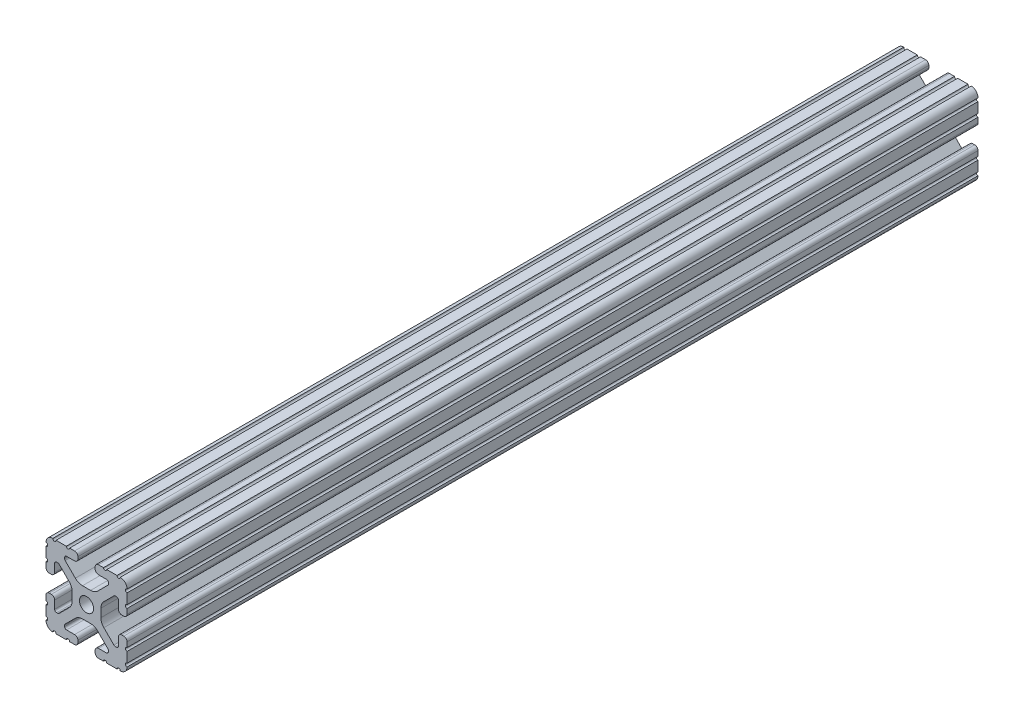
SolidWorks part; units mm, degrees
ref_plane "Front Plane" through (0, 0, 0) normal (0, 0, 1) x (1, 0, 0)
ref_plane "Top Plane" through (0, 0, 0) normal (0, 1, 0) x (1, 0, 0)
ref_plane "Right Plane" through (0, 0, 0) normal (1, 0, 0) x (0, 0, -1)
ref_plane "Plane1" through (0, 0, -304.8) normal (0, 0, -1) x (-1, 0, 0)
sketch "Sketch1" plane through (0, 0, -304.8) normal (0, 0, -1) x (-1, 0, 0)
  line L0 (14.3277, 19.05) -> (9.4982, 19.05)
  line L1 (7.9742, 19.05) -> (5.6176, 19.05)
  line L2 (4.064, 17.4964) -> (4.064, 16.5396)
  line L3 (5.6176, 14.986) -> (9.3853, 14.986)
  line L4 (10.287, 14.0843) -> (10.287, 13.5524)
  line L5 (10.0229, 12.9148) -> (5.2522, 8.144)
  line L6 (1.9022, 6.7564) -> (-1.9022, 6.7564)
  line L7 (-5.2522, 8.144) -> (-10.0229, 12.9148)
  line L8 (-10.287, 13.5524) -> (-10.287, 14.0843)
  line L9 (-9.3853, 14.986) -> (-5.6176, 14.986)
  line L10 (-4.064, 16.5396) -> (-4.064, 17.4964)
  line L11 (-5.6176, 19.05) -> (-7.9742, 19.05)
  line L12 (-9.4982, 19.05) -> (-14.3277, 19.05)
  line L13 (-19.05, 14.3277) -> (-19.05, 9.4961)
  line L14 (-19.05, 7.9763) -> (-19.05, 5.6176)
  line L15 (-17.4964, 4.064) -> (-16.5396, 4.064)
  line L16 (-14.986, 5.6176) -> (-14.986, 9.3853)
  line L17 (-14.0843, 10.287) -> (-13.516, 10.287)
  line L18 (-12.8784, 10.0229) -> (-8.1476, 5.2921)
  line L19 (-6.7564, 1.9335) -> (-6.7564, -1.9335)
  line L20 (-8.1476, -5.2921) -> (-12.8784, -10.0229)
  line L21 (-13.516, -10.287) -> (-14.0843, -10.287)
  line L22 (-14.986, -9.3853) -> (-14.986, -5.6176)
  line L23 (-16.5396, -4.064) -> (-17.4964, -4.064)
  line L24 (-19.05, -5.6176) -> (-19.05, -7.9763)
  line L25 (-19.05, -9.4961) -> (-19.05, -14.3277)
  line L26 (-14.3277, -19.05) -> (-9.4961, -19.05)
  line L27 (-7.9763, -19.05) -> (-5.6176, -19.05)
  line L28 (-4.064, -17.4964) -> (-4.064, -16.5396)
  line L29 (-5.6176, -14.986) -> (-9.3853, -14.986)
  line L30 (-10.287, -14.0843) -> (-10.287, -13.5524)
  line L31 (-10.0229, -12.9148) -> (-5.2522, -8.144)
  line L32 (-1.9022, -6.7564) -> (1.9022, -6.7564)
  line L33 (5.2522, -8.144) -> (10.0229, -12.9148)
  line L34 (10.287, -13.5524) -> (10.287, -14.0843)
  line L35 (9.3853, -14.986) -> (5.6176, -14.986)
  line L36 (4.064, -16.5396) -> (4.064, -17.4964)
  line L37 (5.6176, -19.05) -> (7.9763, -19.05)
  line L38 (9.4961, -19.05) -> (14.3277, -19.05)
  line L39 (19.05, -14.3277) -> (19.05, -9.4961)
  line L40 (19.05, -7.9763) -> (19.05, -5.6176)
  line L41 (17.4964, -4.064) -> (16.5396, -4.064)
  line L42 (14.986, -5.6176) -> (14.986, -9.3853)
  line L43 (14.0843, -10.287) -> (13.516, -10.287)
  line L44 (12.8784, -10.0229) -> (8.1476, -5.2921)
  line L45 (6.7564, -1.9335) -> (6.7564, 1.9335)
  line L46 (8.1476, 5.2921) -> (12.8784, 10.0229)
  line L47 (13.516, 10.287) -> (14.0843, 10.287)
  line L48 (14.986, 9.3853) -> (14.986, 5.6176)
  line L49 (16.5396, 4.064) -> (17.4964, 4.064)
  line L50 (19.05, 5.6176) -> (19.05, 7.9763)
  line L51 (19.05, 9.4961) -> (19.05, 14.3277)
  line L52 (19.05, 5.6176) -> (17.4964, 5.6176) construction
  line L53 (17.4964, 5.6176) -> (17.4964, 4.064) construction
  line L54 (17.4964, 5.6176) -> (18.5393, 4.466) construction
  arc A0 (15.8475, 19.05) -> (14.3277, 19.05) centre (15.0876, 18.9933) cw
  arc A1 (9.4982, 19.05) -> (7.9742, 19.05) centre (8.7362, 19.05) cw
  arc A2 (5.6176, 19.05) -> (4.064, 17.4964) centre (5.6176, 17.4964) ccw
  arc A3 (4.064, 16.5396) -> (5.6176, 14.986) centre (5.6176, 16.5396) ccw
  arc A4 (9.3853, 14.986) -> (10.287, 14.0843) centre (9.3853, 14.0843) cw
  arc A5 (10.287, 13.5524) -> (10.0229, 12.9148) centre (9.3853, 13.5524) cw
  arc A6 (5.2522, 8.144) -> (1.9022, 6.7564) centre (1.9022, 11.494) cw
  arc A7 (-1.9022, 6.7564) -> (-5.2522, 8.144) centre (-1.9022, 11.494) cw
  arc A8 (-10.0229, 12.9148) -> (-10.287, 13.5524) centre (-9.3853, 13.5524) cw
  arc A9 (-10.287, 14.0843) -> (-9.3853, 14.986) centre (-9.3853, 14.0843) cw
  arc A10 (-5.6176, 14.986) -> (-4.064, 16.5396) centre (-5.6176, 16.5396) ccw
  arc A11 (-4.064, 17.4964) -> (-5.6176, 19.05) centre (-5.6176, 17.4964) ccw
  arc A12 (-7.9742, 19.05) -> (-9.4982, 19.05) centre (-8.7362, 19.05) cw
  arc A13 (-14.3277, 19.05) -> (-15.8475, 19.05) centre (-15.0876, 18.9933) cw
  arc A14 (-15.8475, 19.05) -> (-19.05, 15.8475) centre (-15.8751, 15.8751) ccw
  arc A15 (-19.05, 15.8475) -> (-19.05, 14.3277) centre (-18.9933, 15.0876) cw
  arc A16 (-19.05, 9.4961) -> (-19.05, 7.9763) centre (-18.9933, 8.7362) cw
  arc A17 (-19.05, 5.6176) -> (-17.4964, 4.064) centre (-17.4964, 5.6176) ccw
  arc A18 (-16.5396, 4.064) -> (-14.986, 5.6176) centre (-16.5396, 5.6176) ccw
  arc A19 (-14.986, 9.3853) -> (-14.0843, 10.287) centre (-14.0843, 9.3853) cw
  arc A20 (-13.516, 10.287) -> (-12.8784, 10.0229) centre (-13.516, 9.3853) cw
  arc A21 (-8.1476, 5.2921) -> (-6.7564, 1.9335) centre (-11.5062, 1.9335) cw
  arc A22 (-6.7564, -1.9335) -> (-8.1476, -5.2921) centre (-11.5062, -1.9335) cw
  arc A23 (-12.8784, -10.0229) -> (-13.516, -10.287) centre (-13.516, -9.3853) cw
  arc A24 (-14.0843, -10.287) -> (-14.986, -9.3853) centre (-14.0843, -9.3853) cw
  arc A25 (-14.986, -5.6176) -> (-16.5396, -4.064) centre (-16.5396, -5.6176) ccw
  arc A26 (-17.4964, -4.064) -> (-19.05, -5.6176) centre (-17.4964, -5.6176) ccw
  arc A27 (-19.05, -7.9763) -> (-19.05, -9.4961) centre (-18.9933, -8.7362) cw
  arc A28 (-19.05, -14.3277) -> (-19.05, -15.8475) centre (-18.9933, -15.0876) cw
  arc A29 (-19.05, -15.8475) -> (-15.8475, -19.05) centre (-15.8751, -15.8751) ccw
  arc A30 (-15.8475, -19.05) -> (-14.3277, -19.05) centre (-15.0876, -18.9933) cw
  arc A31 (-9.4961, -19.05) -> (-7.9763, -19.05) centre (-8.7362, -18.9933) cw
  arc A32 (-5.6176, -19.05) -> (-4.064, -17.4964) centre (-5.6176, -17.4964) ccw
  arc A33 (-4.064, -16.5396) -> (-5.6176, -14.986) centre (-5.6176, -16.5396) ccw
  arc A34 (-9.3853, -14.986) -> (-10.287, -14.0843) centre (-9.3853, -14.0843) cw
  arc A35 (-10.287, -13.5524) -> (-10.0229, -12.9148) centre (-9.3853, -13.5524) cw
  arc A36 (-5.2522, -8.144) -> (-1.9022, -6.7564) centre (-1.9022, -11.494) cw
  arc A37 (1.9022, -6.7564) -> (5.2522, -8.144) centre (1.9022, -11.494) cw
  arc A38 (10.0229, -12.9148) -> (10.287, -13.5524) centre (9.3853, -13.5524) cw
  arc A39 (10.287, -14.0843) -> (9.3853, -14.986) centre (9.3853, -14.0843) cw
  arc A40 (5.6176, -14.986) -> (4.064, -16.5396) centre (5.6176, -16.5396) ccw
  arc A41 (4.064, -17.4964) -> (5.6176, -19.05) centre (5.6176, -17.4964) ccw
  arc A42 (7.9763, -19.05) -> (9.4961, -19.05) centre (8.7362, -18.9933) cw
  arc A43 (14.3277, -19.05) -> (15.8475, -19.05) centre (15.0876, -18.9933) cw
  arc A44 (15.8475, -19.05) -> (19.05, -15.8475) centre (15.8751, -15.8751) ccw
  arc A45 (19.05, -15.8475) -> (19.05, -14.3277) centre (18.9933, -15.0876) cw
  arc A46 (19.05, -9.4961) -> (19.05, -7.9763) centre (18.9933, -8.7362) cw
  arc A47 (19.05, -5.6176) -> (17.4964, -4.064) centre (17.4964, -5.6176) ccw
  arc A48 (16.5396, -4.064) -> (14.986, -5.6176) centre (16.5396, -5.6176) ccw
  arc A49 (14.986, -9.3853) -> (14.0843, -10.287) centre (14.0843, -9.3853) cw
  arc A50 (13.516, -10.287) -> (12.8784, -10.0229) centre (13.516, -9.3853) cw
  arc A51 (8.1476, -5.2921) -> (6.7564, -1.9335) centre (11.5062, -1.9335) cw
  arc A52 (6.7564, 1.9335) -> (8.1476, 5.2921) centre (11.5062, 1.9335) cw
  arc A53 (12.8784, 10.0229) -> (13.516, 10.287) centre (13.516, 9.3853) cw
  arc A54 (14.0843, 10.287) -> (14.986, 9.3853) centre (14.0843, 9.3853) cw
  arc A55 (14.986, 5.6176) -> (16.5396, 4.064) centre (16.5396, 5.6176) ccw
  arc A56 (17.4964, 4.064) -> (19.05, 5.6176) centre (17.4964, 5.6176) ccw
  arc A57 (19.05, 7.9763) -> (19.05, 9.4961) centre (18.9933, 8.7362) cw
  arc A58 (19.05, 14.3277) -> (19.05, 15.8475) centre (18.9933, 15.0876) cw
  arc A59 (19.05, 15.8475) -> (15.8475, 19.05) centre (15.8751, 15.8751) ccw
  circle A60 centre (0, 0) radius 3.3274
sketch "Sketch2" plane through (0, 0, 0) normal (0, 1, 0) x (1, 0, 0)
  line L0 (0, 304.8) -> (0, -95.2)
  dimension "D1" = 400
sweep "Sweep1" add profiles "Sketch1" path "Sketch2"
ref_point "Front"
ref_point "Back"
curve "Centerline"
